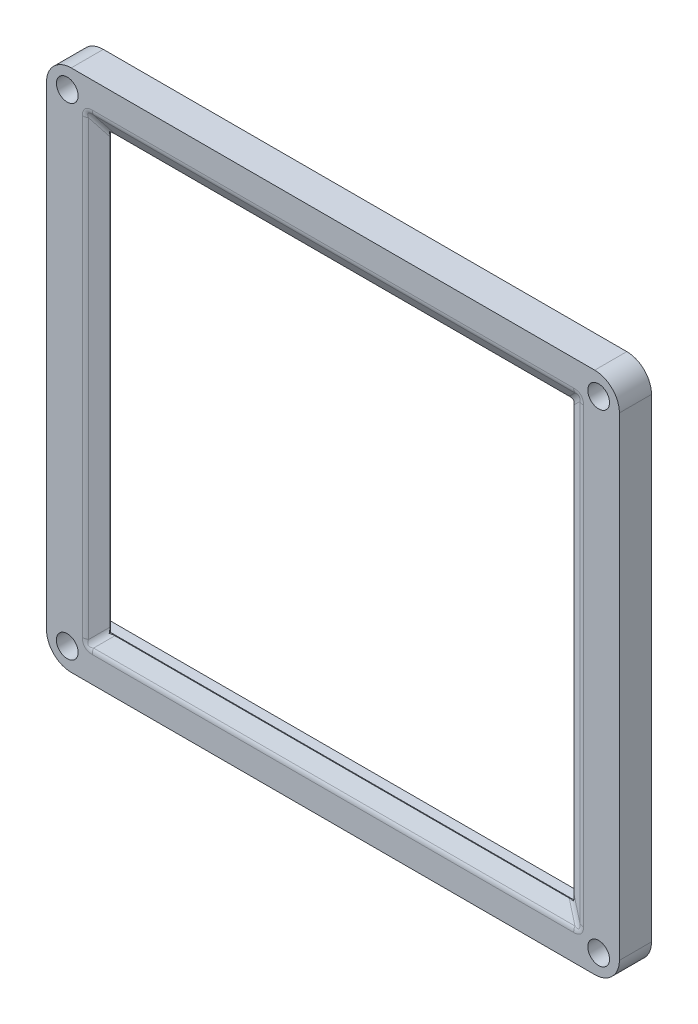
SolidWorks part; units mm, degrees
ref_plane "前视基准面" through (0, 0, 0) normal (0, 0, 1) x (1, 0, 0)
ref_plane "上视基准面" through (0, 0, 0) normal (0, 1, 0) x (1, 0, 0)
ref_plane "右视基准面" through (0, 0, 0) normal (1, 0, 0) x (0, 0, -1)
sketch "草图1" plane through (0, 0, 0) normal (0, 0, 1) x (1, 0, 0)
  line L0 (-1000, 0) -> (49000, 0) construction
  line L1 (-26.5, -26.5) -> (26.5, -26.5)
  line L2 (-29, -24) -> (-29, 24)
  line L3 (-26.5, 26.5) -> (26.5, 26.5)
  line L4 (29, -24) -> (29, 24)
  line L5 (-29, -26.5) -> (29, 26.5) construction
  line L6 (-29, 26.5) -> (29, -26.5) construction
  line L7 (23.5, -22) -> (-23.5, -22)
  line L8 (23.5, -22) -> (23.5, 22)
  line L9 (23.5, 22) -> (-23.5, 22)
  line L10 (-23.5, -22) -> (-23.5, 22)
  line L11 (23.5, -22) -> (-23.5, 22) construction
  line L12 (23.5, 22) -> (-23.5, -22) construction
  line L13 (0, -1000) -> (0, 49000) construction
  line L15 (-25.75, -23.25) -> (25.75, -23.25) construction
  line L16 (-25.75, -23.25) -> (-25.75, 23.25) construction
  line L17 (-25.75, 23.25) -> (25.75, 23.25) construction
  line L18 (25.75, -23.25) -> (25.75, 23.25) construction
  line L19 (-25.75, -23.25) -> (25.75, 23.25) construction
  line L20 (-25.75, 23.25) -> (25.75, -23.25) construction
  arc A0 (26.5, 26.5) -> (29, 24) centre (26.5, 24) cw
  arc A1 (26.5, -26.5) -> (29, -24) centre (26.5, -24) ccw
  arc A2 (-26.5, -26.5) -> (-29, -24) centre (-26.5, -24) cw
  arc A3 (-29, 24) -> (-26.5, 26.5) centre (-26.5, 24) cw
  circle A4 centre (-26.9, 24.4) radius 1.1
  circle A5 centre (26.9, 24.4) radius 1.1
  circle A6 centre (-26.9, -24.4) radius 1.1
  circle A7 centre (26.9, -24.4) radius 1.1
  point P0 (0, 0)
  point P18 (0, 0)
  point P35 (0, 0)
  dimension "D3" = 2.5
  dimension "D6" = 2.2
  dimension "D1" = 58
  dimension "D2" = 53
  dimension "D4" = 47
  dimension "D5" = 44
  dimension "D7" = 47
  dimension "D8" = 2.1
  dimension "D9" = 2.1
  dimension "D10" = 46.5
  dimension "D11" = 51.5
extrude "凸台-拉伸1" add sketch "草图1" along normal blind 1
sketch "草图2" plane through (0, 0, 0) normal (0, 0, -1) x (-1, 0, 0)
  line L4 (-29, 24) -> (-29, -24)
  line L5 (-26.5, -26.5) -> (26.5, -26.5)
  line L6 (29, -24) -> (29, 24)
  line L7 (26.5, 26.5) -> (-26.5, 26.5)
  line L8 (-29, 24) -> (-29, -24)
  line L9 (-26.5, -26.5) -> (26.5, -26.5)
  line L10 (29, -24) -> (29, 24)
  line L11 (26.5, 26.5) -> (-26.5, 26.5)
  line L13 (-25.75, -23.25) -> (25.75, -23.25)
  line L14 (-25.75, -23.25) -> (-25.75, 23.25)
  line L15 (-25.75, 23.25) -> (25.75, 23.25)
  line L16 (25.75, -23.25) -> (25.75, 23.25)
  line L17 (-25.75, -23.25) -> (25.75, 23.25) construction
  line L18 (-25.75, 23.25) -> (25.75, -23.25) construction
  circle A0 centre (-26.9, 24.4) radius 1.1 construction
  circle A1 centre (-26.9, 24.4) radius 1.1
  arc A4 (-26.5, 26.5) -> (-29, 24) centre (-26.5, 24) ccw
  arc A5 (-29, -24) -> (-26.5, -26.5) centre (-26.5, -24) ccw
  arc A6 (26.5, -26.5) -> (29, -24) centre (26.5, -24) ccw
  arc A7 (29, 24) -> (26.5, 26.5) centre (26.5, 24) ccw
  arc A8 (-26.5, 26.5) -> (-29, 24) centre (-26.5, 24) ccw
  arc A9 (-29, -24) -> (-26.5, -26.5) centre (-26.5, -24) ccw
  arc A10 (26.5, -26.5) -> (29, -24) centre (26.5, -24) ccw
  arc A11 (29, 24) -> (26.5, 26.5) centre (26.5, 24) ccw
  circle A14 centre (-26.9, -24.4) radius 1.1 construction
  circle A15 centre (26.9, -24.4) radius 1.1 construction
  circle A16 centre (26.9, 24.4) radius 1.1 construction
  circle A17 centre (-26.9, -24.4) radius 1.1
  circle A18 centre (26.9, -24.4) radius 1.1
  circle A19 centre (26.9, 24.4) radius 1.1
  point P24 (0, 0)
  circle M11 centre (26.9, -24.4) radius 1.1
  circle M12 centre (26.9, 24.4) radius 1.1
  arc M13 (-26.5, 26.5) -> (-29, 24) centre (-26.5, 24) ccw
  line M14 (-29, 24) -> (-29, -24)
  arc M15 (-29, -24) -> (-26.5, -26.5) centre (-26.5, -24) ccw
  line M16 (-26.5, -26.5) -> (26.5, -26.5)
  arc M17 (26.5, -26.5) -> (29, -24) centre (26.5, -24) ccw
  line M18 (29, -24) -> (29, 24)
  arc M19 (29, 24) -> (26.5, 26.5) centre (26.5, 24) ccw
  line M20 (26.5, 26.5) -> (-26.5, 26.5)
  circle M25 centre (-26.9, 24.4) radius 1.1
  circle M26 centre (-26.9, -24.4) radius 1.1
  dimension "D2" = 51.5
  dimension "D3" = 46.5
  dimension "D1" = 0
extrude "凸台-拉伸2" add sketch "草图2" along normal blind 2.25 contours L16 L13 L14 L15 M20 M13 M14 M15 M16 M17 M18 M19 M11 M26 M25 M12
chamfer "倒角1" distance 1.6 angle 30 4 edges at (0, -22, 1) (23.5, 0, 1) (0, 22, 1) (-23.5, 0, 1)
fillet "圆角1" radius 1 8 edges at (24.3, -22.8, 0.5381) (0, -23.6, 1) (-24.3, -22.8, 0.5381) (25.1, 0, 1) (24.3, 22.8, 0.5381) (-24.3, 22.8, 0.5381) (-25.1, 0, 1) (0, 23.6, 1)
